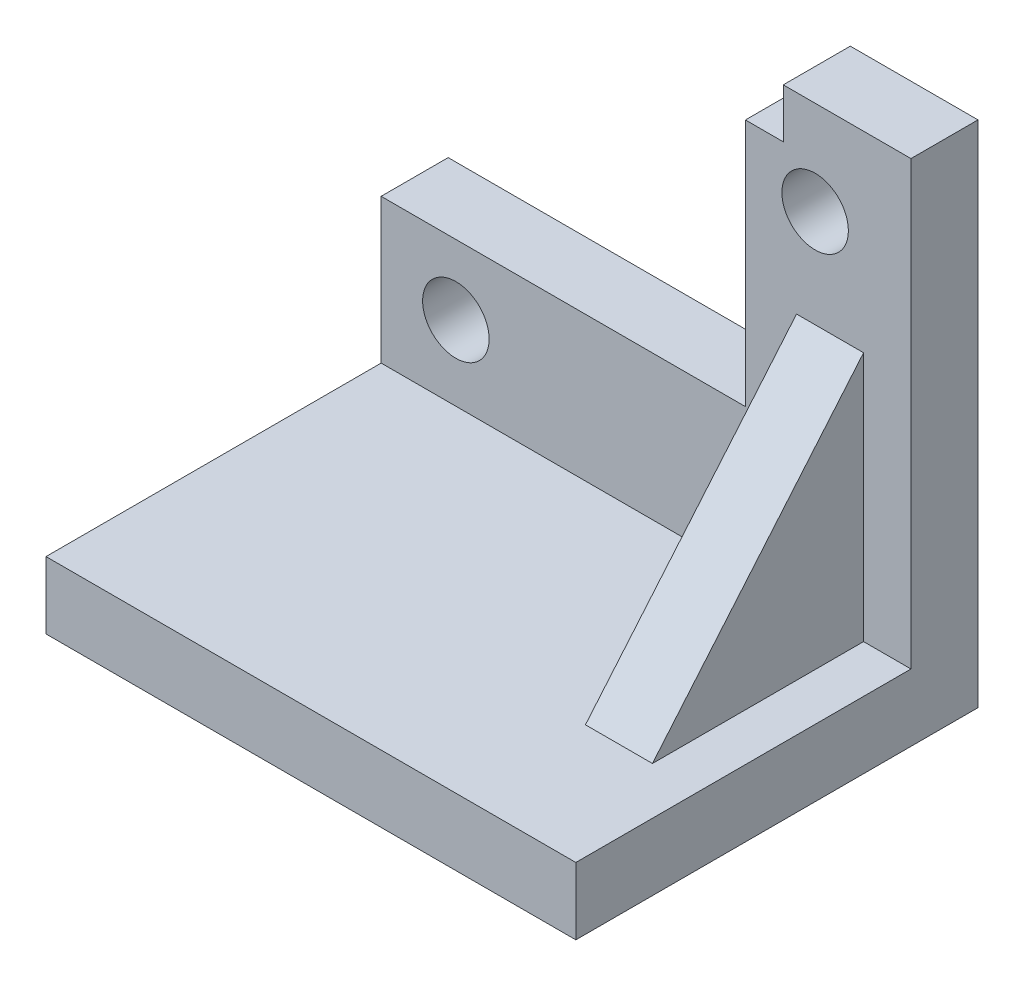
SolidWorks part; units mm, degrees
ref_plane "Front Plane" through (0, 0, 0) normal (0, 0, 1) x (1, 0, 0)
ref_plane "Top Plane" through (0, 0, 0) normal (0, 1, 0) x (1, 0, 0)
ref_plane "Right Plane" through (0, 0, 0) normal (1, 0, 0) x (0, 0, -1)
sketch "Sketch2" plane through (0, 0, 0) normal (0, 0, 1) x (1, 0, 0)
  line L0 (4.3952, 7.8274) -> (4.3952, -1.4384)
  line L1 (4.3952, -1.4384) -> (-11.8608, -1.4384)
  line L2 (-11.8608, -1.4384) -> (-11.8608, -8.2804)
  line L3 (-11.8608, -8.2804) -> (12.2372, -8.2804)
  line L4 (12.2372, -8.2804) -> (12.2372, 12.6586)
  line L5 (12.2372, 12.6586) -> (7.6972, 12.6586)
  line L7 (7.6972, 12.6586) -> (6.1882, 12.6586)
  line L8 (-11.8608, -1.4384) -> (-12.8608, -1.4384)
  line L9 (-11.8608, -1.4384) -> (-11.8608, -8.2804)
  line L10 (-11.8608, -8.2804) -> (-12.8608, -8.2804)
  line L11 (-12.8608, -1.4384) -> (-12.8608, -8.2804)
  line L12 (4.3952, 10.3218) -> (4.3952, 7.8274)
  line L13 (4.3952, 10.3218) -> (6.1882, 10.3218)
  line L14 (6.1882, 10.3218) -> (6.1882, 12.6586)
  circle A0 centre (7.6972, 8.2136) radius 1.5748
  circle A1 centre (-9.3208, -4.7404) radius 1.5748
  point P0 (6.4597, 9.1875)
  dimension "D5" = 16.494
  dimension "D1" = 1
  dimension "D2" = 6.842
  dimension "D3" = 20.939
  dimension "D4" = 24.098
  dimension "D6" = 2.54
  dimension "D7" = 3.54
  dimension "D8" = 17.018
extrude "Boss-Extrude1" add sketch "Sketch2" along normal blind 3.175 contours A0 | L3 L4 L5 L7 L14 L13 L12 L0 L1 L2 | A1
sketch "Sketch5" plane through (0, 0, 0) normal (0, 0, -1) x (-1, 0, 0)
  line L1 (-12.2372, -8.2804) -> (11.8608, -8.2804)
  line L2 (-12.2372, -8.2804) -> (-12.2372, -11.4554)
  line L3 (-12.2372, -11.4554) -> (11.8608, -11.4554)
  line L4 (11.8608, -8.2804) -> (11.8608, -11.4554)
  line L5 (11.8608, -1.4384) -> (11.8608, -8.2804) construction
  dimension "D1" = 3.175
extrude "Boss-Extrude2" add sketch "Sketch5" against normal blind 19.05
sketch "Sketch7" plane through (0, 0, 3.175) normal (0, 0, 1) x (1, 0, 0)
  line L0 (-11.8608, -1.4384) -> (-11.8608, -8.2804) construction
  line L1 (-11.8608, -1.4384) -> (-12.8608, -1.4384)
  line L2 (-11.8608, -1.4384) -> (-11.8608, -8.2804)
  line L3 (-11.8608, -8.2804) -> (-12.8608, -8.2804)
  line L4 (-12.8608, -1.4384) -> (-12.8608, -8.2804)
  dimension "D1" = 1
extrude "Boss-Extrude3" add sketch "Sketch7" against normal blind 3.175
sketch "Sketch8" plane through (0, 0, 19.05) normal (0, 0, 1) x (1, 0, 0)
  line L1 (-11.8608, -11.4554) -> (-12.8608, -11.4554)
  line L2 (-11.8608, -11.4554) -> (-11.8608, -8.2804)
  line L3 (-11.8608, -8.2804) -> (-12.8608, -8.2804)
  line L4 (-12.8608, -11.4554) -> (-12.8608, -8.2804)
extrude "Boss-Extrude4" add sketch "Sketch8" against normal blind 19.05
sketch "Sketch9" plane through (0, 0, 3.175) normal (0, 0, 1) x (1, 0, 0)
  line L0 (6.8165, -8.2804) -> (9.9915, -8.2804)
  line L1 (9.9915, -8.2804) -> (9.9915, 3.57)
  line L2 (-12.8608, -8.2804) -> (12.2372, -8.2804) construction
  line L3 (9.9915, 3.57) -> (6.8165, 3.57)
  line L4 (6.8165, 3.57) -> (6.8165, -8.2804)
  line L6 (12.2372, -8.2804) -> (12.2372, 12.6586) construction
  dimension "D1" = 3.175
  dimension "D2" = 2.2457
extrude "Boss-Extrude5" add sketch "Sketch9" along normal blind 10
sketch "Sketch10" plane through (9.9915, 0, 0) normal (1, 0, 0) x (0, 0, -1)
  line L0 (-3.175, 3.57) -> (-13.175, -8.2804)
  line L1 (-3.175, 3.57) -> (-13.175, 3.57)
  line L2 (-13.175, 3.57) -> (-13.175, -8.2804)
extrude "Cut-Extrude1" cut sketch "Sketch10" against normal through all
